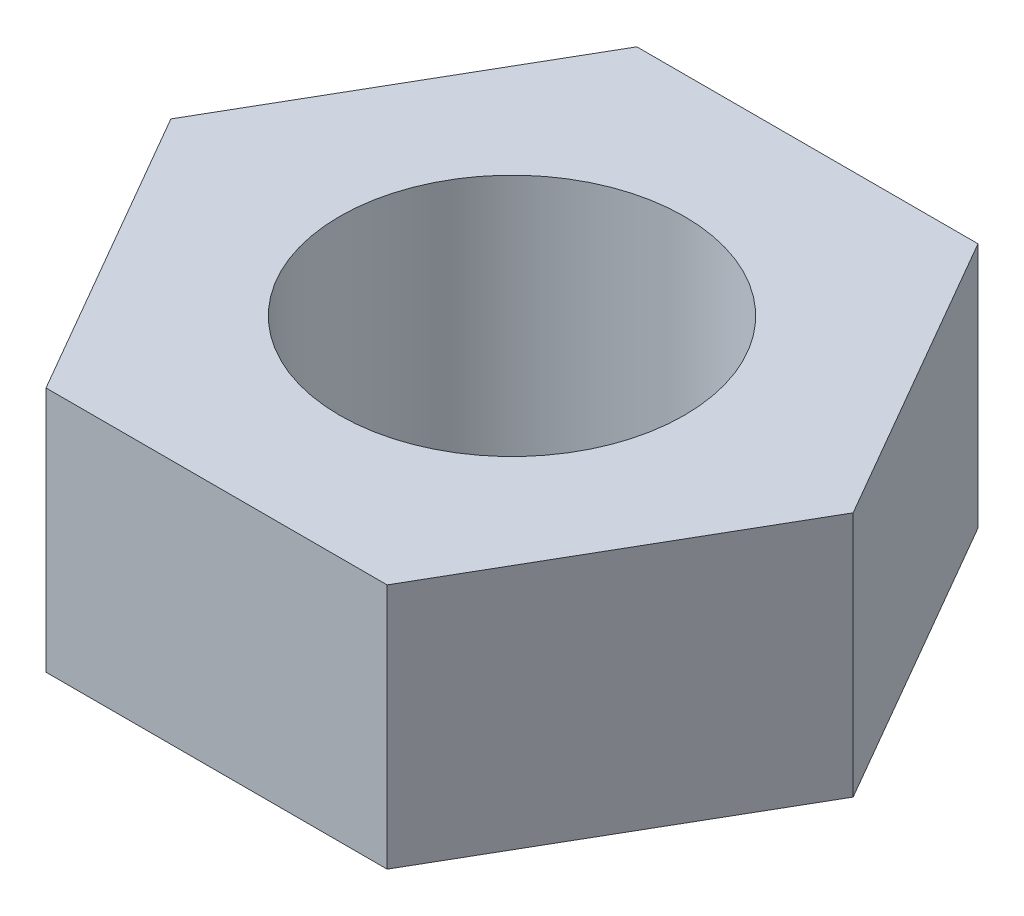
SolidWorks part; units mm, degrees
ref_plane "Front Plane" through (0, 0, 0) normal (0, 0, 1) x (1, 0, 0)
ref_plane "Top Plane" through (0, 0, 0) normal (0, 1, 0) x (1, 0, 0)
ref_plane "Right Plane" through (0, 0, 0) normal (1, 0, 0) x (0, 0, -1)
sketch "Sketch2" plane through (0, 0, 0) normal (0, 1, 0) x (1, 0, 0)
  line L1 (6.9282, 12) -> (-6.9282, 12)
  line L2 (-6.9282, 12) -> (-13.8564, 0)
  line L3 (-13.8564, 0) -> (-6.9282, -12)
  line L4 (-6.9282, -12) -> (6.9282, -12)
  line L5 (6.9282, -12) -> (13.8564, 0)
  line L6 (13.8564, 0) -> (6.9282, 12)
  circle A0 centre (0, 0) radius 12 construction
  circle A1 centre (0, 0) radius 7
  dimension "D2" = 14
  dimension "D1" = 24
extrude "Boss-Extrude1" add sketch "Sketch2" against normal blind 10
